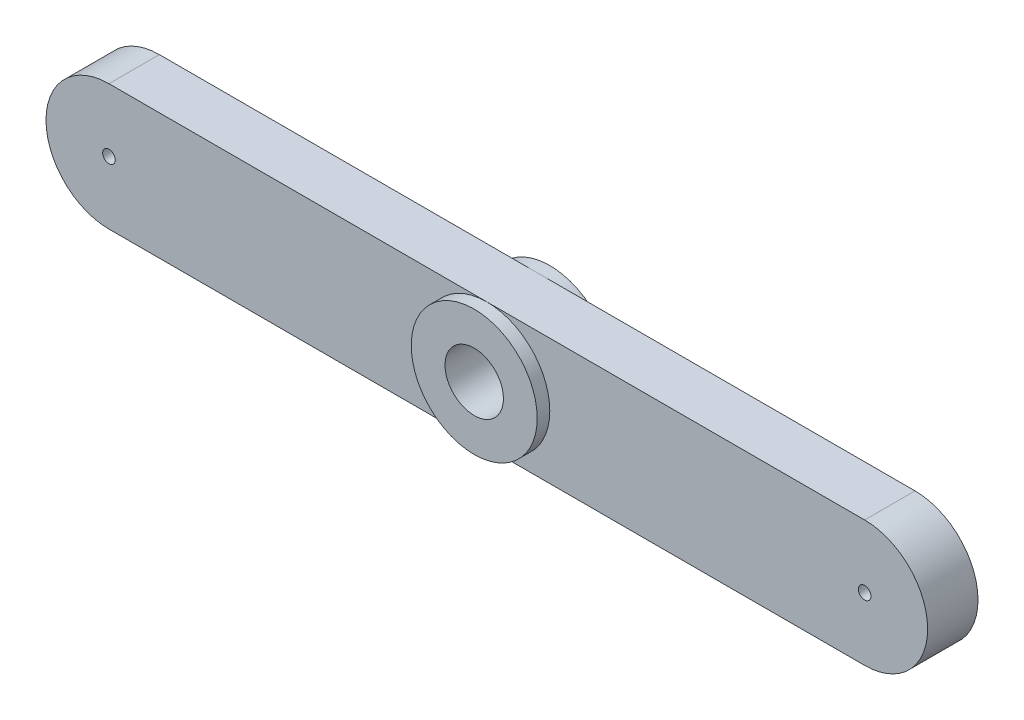
SolidWorks part; units mm, degrees
ref_plane "Front Plane" through (0, 0, 0) normal (0, 0, 1) x (1, 0, 0)
ref_plane "Top Plane" through (0, 0, 0) normal (0, 1, 0) x (1, 0, 0)
ref_plane "Right Plane" through (0, 0, 0) normal (1, 0, 0) x (0, 0, -1)
sketch "Sketch1" plane through (0, 0, 0) normal (0, 0, 1) x (1, 0, 0)
  line L1 (-15, -2.5) -> (15, -2.5)
  line L2 (-15, -2.5) -> (-15, 2.5)
  line L3 (-15, 2.5) -> (15, 2.5)
  line L4 (15, -2.5) -> (15, 2.5)
  line L5 (-15, -2.5) -> (15, 2.5) construction
  line L6 (-15, 2.5) -> (15, -2.5) construction
  circle A0 centre (0, 0) radius 1.1595
  circle A1 centre (0, 0) radius 2.5
  circle A2 centre (15, 0) radius 2.5
  circle A3 centre (-15, 0) radius 2.5
  circle A4 centre (-15, 0) radius 0.25
  circle A5 centre (15, 0) radius 0.25
  point P14 (15.6057, 0)
  dimension "D1" = 30
  dimension "D3" = 5
  dimension "D4" = 0.5
  dimension "D5" = 0.5
  dimension "D2" = 5
extrude "Boss-Extrude2" add sketch "Sketch1" along normal mid plane 2 contours A3 L1 A1 L3 | A4 L2 A3 | A4 L2 A3 | A2 L3 A1 L1 | A5 L4 A2 | A5 L4 A2
sketch "Sketch2" plane through (0, 0, 0) normal (0, 0, 1) x (1, 0, 0)
  circle A0 centre (0, 0) radius 1.1595
  circle A1 centre (0, 0) radius 2.5
extrude "Boss-Extrude3" add sketch "Sketch2" along normal mid plane 3
